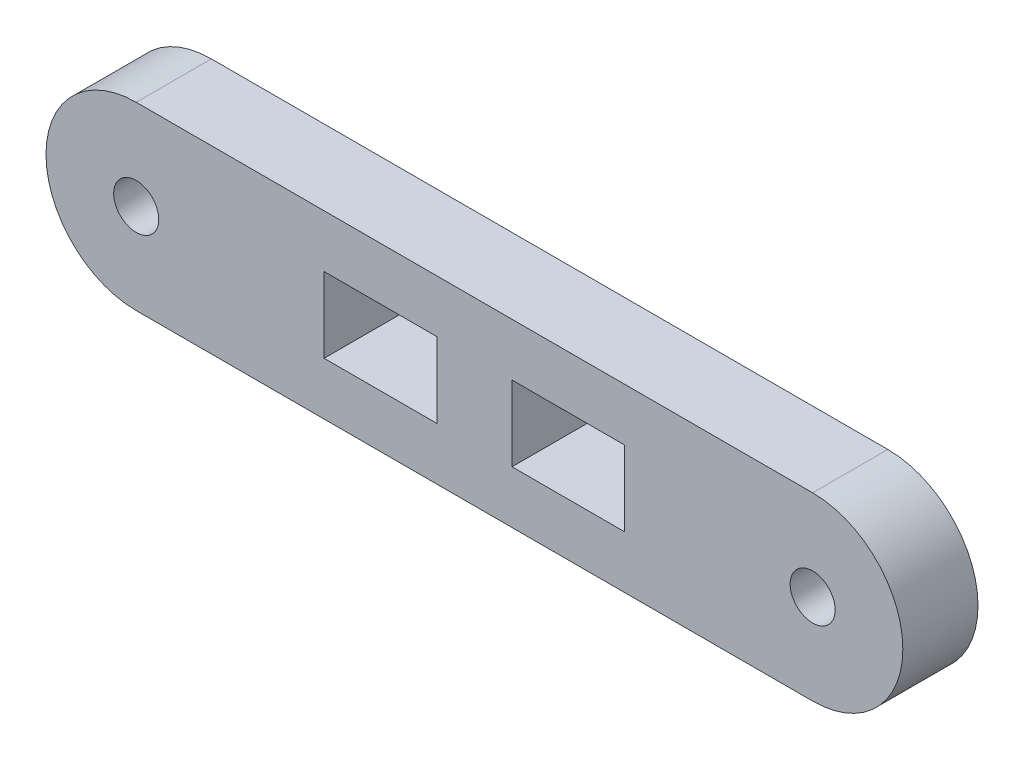
SolidWorks part; units mm, degrees
ref_plane "Plan de face" through (0, 0, 0) normal (0, 0, 1) x (1, 0, 0)
ref_plane "Plan de dessus" through (0, 0, 0) normal (0, 1, 0) x (1, 0, 0)
ref_plane "Plan de droite" through (0, 0, 0) normal (1, 0, 0) x (0, 0, -1)
sketch "Esquisse1" plane through (0, 0, 0) normal (0, 0, 1) x (1, 0, 0)
  line L0 (22.5, 6) -> (22.5, -6) construction
  line L2 (0, 0) -> (45, 0) construction
  line L4 (32.5, -2.5) -> (25, -2.5)
  line L5 (25, -2.5) -> (25, 2.5)
  line L6 (25, 2.5) -> (32.5, 2.5)
  line L7 (32.5, 2.5) -> (32.5, -2.5)
  line L8 (12.5, 2.5) -> (12.5, -2.5)
  line L9 (20, 2.5) -> (12.5, 2.5)
  line L10 (20, -2.5) -> (20, 2.5)
  line L11 (12.5, -2.5) -> (20, -2.5)
  line L12 (0, 0) -> (45, 0) construction
  line L13 (0, 6) -> (45, 6)
  line L14 (0, -6) -> (45, -6)
  arc A0 (0, 6) -> (0, -6) centre (0, 0) ccw
  arc A1 (45, -6) -> (45, 6) centre (45, 0) ccw
  circle A5 centre (45, 0) radius 1.5
  circle A6 centre (0, 0) radius 1.5
  point P0 (22.5, 0)
  dimension "D1" = 6
  dimension "D2" = 3
  dimension "D3" = 5
  dimension "D4" = 45
  dimension "D6" = 7.5
  dimension "D7" = 5
extrude "Boss.-Extru.1" add sketch "Esquisse1" along normal blind 5
